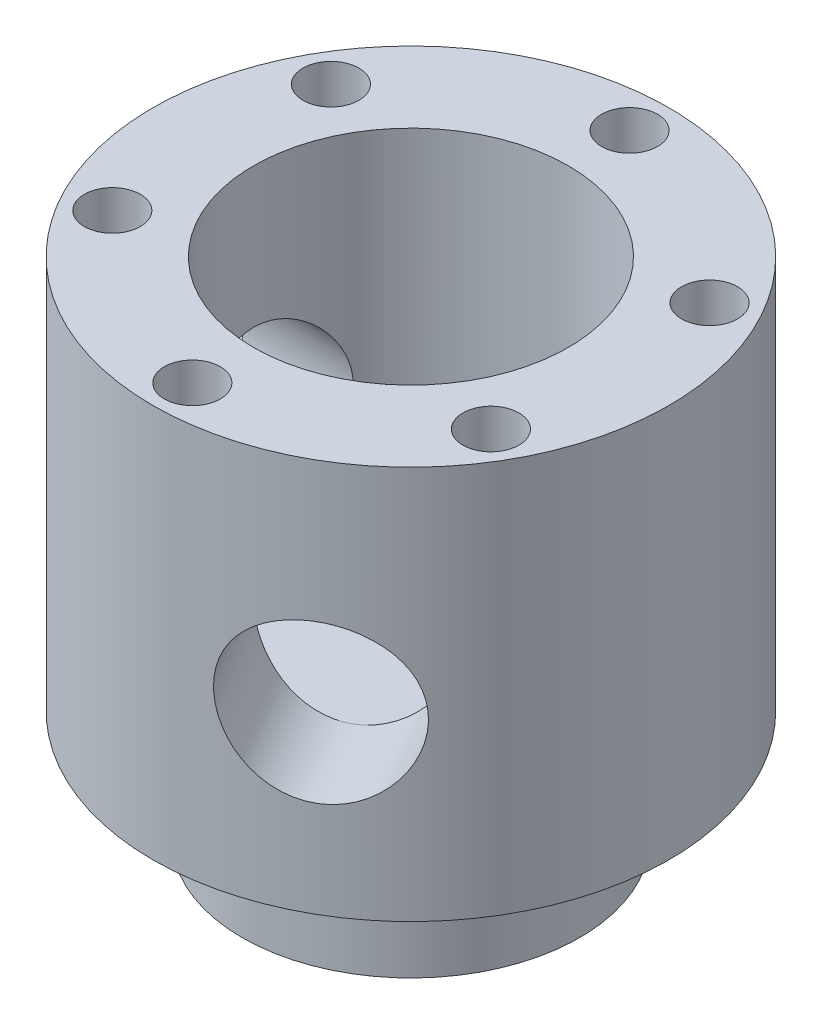
SolidWorks part; units mm, degrees
material "ABS"
ref_plane "前视基准面" through (0, 0, 0) normal (0, 0, 1) x (1, 0, 0)
ref_plane "上视基准面" through (0, 0, 0) normal (0, 1, 0) x (1, 0, 0)
ref_plane "右视基准面" through (0, 0, 0) normal (1, 0, 0) x (0, 0, -1)
other "Configuration Table"
sketch "草图1" plane through (0, 0, 0) normal (0, 1, 0) x (1, 0, 0)
  circle A0 centre (0, 0) radius 14.75
  dimension "D1" = 29.5
extrude "凸台-拉伸1" add sketch "草图1" along normal blind 22.5
sketch "草图3" plane through (0, 0, 0) normal (0, 1, 0) x (1, 0, 0)
  circle A0 centre (0, 0) radius 12.5 construction
  circle A1 centre (0, 12.5) radius 1.6
  circle A2 centre (10.8253, 6.25) radius 1.6
  circle A3 centre (10.8253, -6.25) radius 1.6
  circle A4 centre (0, -12.5) radius 1.6
  circle A5 centre (-10.8253, -6.25) radius 1.6
  circle A6 centre (-10.8253, 6.25) radius 1.6
  dimension "D1" = 25
  dimension "D2" = 3.2
extrude "切除-拉伸1" cut sketch "草图3" along normal through all
sketch "草图5" plane through (0, 0, 0) normal (0, -1, 0) x (1, 0, 0)
  circle A0 centre (0, 0) radius 9.65
  circle A1 centre (0, 0) radius 14.75 construction
  dimension "D1" = 19.3
extrude "凸台-拉伸2" add sketch "草图5" along normal blind 6.4
sketch "草图6" plane through (0, 22.5, 0) normal (0, 1, 0) x (1, 0, 0)
  circle A0 centre (0, 0) radius 9
  dimension "D1" = 18
extrude "切除-拉伸2" cut sketch "草图6" against normal blind 17
sketch "草图9" plane through (0, 0, 0) normal (1, 0, 0) x (0, 0, -1)
  line L0 (0, 22.5) -> (0, 10) construction
  line L1 (14.75, 22.5) -> (-14.75, 22.5) construction
  circle A0 centre (0, 10) radius 4.5
  dimension "D1" = 9
  dimension "D2" = 12.5
extrude "切除-拉伸3" cut sketch "草图9" against normal through all
pattern_circular "阵列(圆周)1" count 3 over 360 about axis through (0, 22.5, 0) along (0, 1, 0) of "切除-拉伸3"
